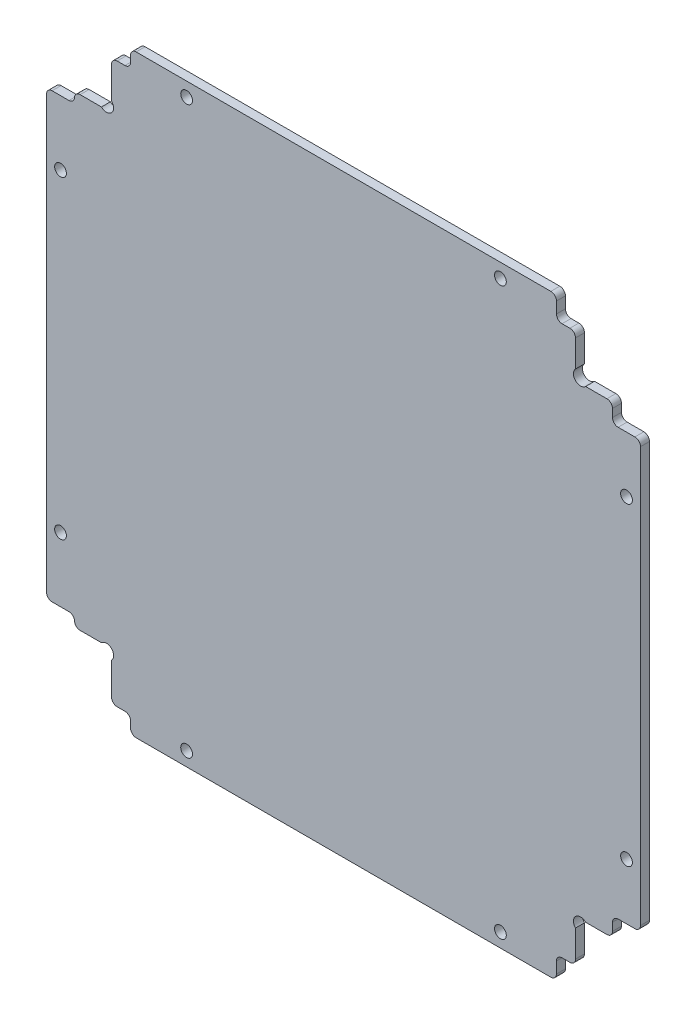
SolidWorks part; units mm, degrees
ref_plane "Front Plane" through (0, 0, 0) normal (0, 0, 1) x (1, 0, 0)
ref_plane "Top Plane" through (0, 0, 0) normal (0, 1, 0) x (1, 0, 0)
ref_plane "Right Plane" through (0, 0, 0) normal (1, 0, 0) x (0, 0, -1)
sketch "Sketch1" plane through (0, 0, 0) normal (0, 0, 1) x (1, 0, 0)
  line L0 (53, 53) -> (-53, -53) construction
  line L1 (53, 53) -> (-53, 53)
  line L2 (53, 53) -> (53, -53)
  line L3 (53, -53) -> (-53, -53)
  line L4 (-53, 53) -> (-53, -53)
  point P4 (0, 0)
  dimension "D1" = 106
  dimension "D2" = 106
extrude "mainOutline" add sketch "Sketch1" along normal blind 1.6
sketch "axisLabels" plane through (0, 0, 0) normal (0, 0, -1) x (-1, 0, 0)
  text T0 "+Y"
  text T1 "+X"
sketch "Sketch4" plane through (0, 0, 0) normal (0, 0, -1) x (-1, 0, 0)
  line L1 (-41.4, -41.4) -> (-48, -41.4)
  line L3 (-41.4, -49) -> (-41.4, -41.4)
  line L5 (-60.1065, -39) -> (-49.9975, -39)
  line L7 (-39, -61.4521) -> (-39, -49.9)
  line L9 (39, -56.2753) -> (39, -49.9)
  line L10 (-53, 53) -> (53, 53) construction
  line L11 (41.4, -49.9) -> (41.4, -41.4)
  line L12 (-53, -53) -> (-53, 53) construction
  line L13 (41.4, -41.4) -> (48, -41.4)
  line L15 (48, -40.5) -> (55.5177, -40.5)
  line L17 (55.3838, 40.5) -> (48, 40.5)
  line L19 (39, 57.6877) -> (39, 49.9)
  line L21 (-39, 59.8804) -> (-39, 49.9)
  line L23 (-56.8428, 39) -> (-49.9975, 39)
  line L25 (-41.4, 41.4) -> (-41.4, 49)
  line L27 (-48, 41.4) -> (-41.4, 41.4)
  line L29 (41.4, 49.9) -> (41.4, 41.4)
  line L31 (48, 41.4) -> (41.4, 41.4)
  line L32 (-48, 41.4) -> (-48, 39)
  line L33 (-48, 39) -> (-49.9975, 39)
  line L34 (-41.4, 49) -> (-39, 49)
  line L35 (-39, 49) -> (-39, 49.9)
  line L36 (48, 40.5) -> (48, 41.4)
  line L37 (39, 49.9) -> (41.4, 49.9)
  line L38 (48, -40.5) -> (48, -41.4)
  line L39 (39, -49.9) -> (41.4, -49.9)
  line L40 (-41.4, -49) -> (-39, -49)
  line L41 (-39, -49) -> (-39, -49.9)
  line L42 (-49.9975, -39) -> (-48, -39)
  line L43 (-48, -39) -> (-48, -41.4)
  line L44 (-39, 59.8804) -> (-56.8428, 59.8804)
  line L45 (-56.8428, 59.8804) -> (-56.8428, 39)
  line L46 (53, 53) -> (53, -53) construction
  line L47 (-60.1065, -39) -> (-60.1065, -61.4521)
  line L48 (-60.1065, -61.4521) -> (-39, -61.4521)
  line L49 (39, -56.2753) -> (55.5177, -56.2753)
  line L50 (55.5177, -56.2753) -> (55.5177, -40.5)
  line L51 (55.3838, 40.5) -> (55.3838, 57.6877)
  line L52 (55.3838, 57.6877) -> (39, 57.6877)
  line L53 (53, -53) -> (-53, -53) construction
  dimension "D1" = 14
  dimension "D2" = 11.6
  dimension "D3" = 5
  dimension "D4" = 12.5
  dimension "D5" = 11.6
  dimension "D6" = 3.1
  dimension "D7" = 12.5
  dimension "D8" = 14
  dimension "D9" = 3.1
  dimension "D10" = 5
  dimension "D11" = 11.6
  dimension "D12" = 11.6
  dimension "D13" = 14
  dimension "D14" = 14
  dimension "D15" = 11.6
  dimension "D16" = 11.6
  dimension "D17" = 5
  dimension "D18" = 4
  dimension "D19" = 14
  dimension "D20" = 14
  dimension "D21" = 11.6
  dimension "D22" = 11.6
  dimension "D23" = 4
  dimension "D24" = 5
extrude "railCutouts" cut sketch "Sketch4" against normal through all
sketch "Sketch5" plane through (0, 0, 0) normal (0, 0, -1) x (-1, 0, 0)
  line L0 (-48.898, -39.898) -> (-52.4015, -43.4015) construction
  line L1 (-48, -40.7961) -> (-51.5035, -44.2995) construction
  line L2 (-49.7961, -39) -> (-53.2995, -42.5035) construction
  line L3 (-48, -41.4) -> (-48, -39) construction
  line L4 (-48, 39) -> (-48, 41.4) construction
  line L5 (-42.298, -42.298) -> (-45.4445, -45.4445) construction
  line L6 (-41.4, -43.1961) -> (-44.5465, -46.3425)
  line L7 (-43.1961, -41.4) -> (-46.3425, -44.5465)
  line L8 (-39.898, -49.898) -> (-42.6199, -52.6199) construction
  line L9 (-39, -50.7961) -> (-41.7219, -53.5179) construction
  line L10 (-40.7961, -49) -> (-43.5179, -51.7219) construction
  line L11 (39.898, -50.798) -> (41.4231, -52.3231) construction
  line L12 (40.7961, -49.9) -> (42.3212, -51.4251) construction
  line L13 (39, -51.6961) -> (40.5251, -53.2212) construction
  line L14 (42.298, -42.298) -> (44.0402, -44.0402) construction
  line L15 (43.1961, -41.4) -> (44.9382, -43.1422)
  line L16 (41.4, -43.1961) -> (43.1422, -44.9382)
  line L17 (48.898, -41.398) -> (49.9793, -42.4793) construction
  line L18 (49.7961, -40.5) -> (50.8774, -41.5813) construction
  line L19 (48, -42.2961) -> (49.0813, -43.3774) construction
  line L20 (48.898, 41.398) -> (50.5001, 43.0001) construction
  line L21 (48, 42.2961) -> (49.602, 43.8981) construction
  line L22 (49.7961, 40.5) -> (51.3981, 42.102) construction
  line L23 (42.298, 42.298) -> (44.029, 44.029) construction
  line L24 (41.4, 43.1961) -> (43.131, 44.927)
  line L25 (43.1961, 41.4) -> (44.927, 43.131)
  line L26 (39.898, 50.798) -> (41.2638, 52.1638) construction
  line L27 (39, 51.6961) -> (40.3658, 53.0618) construction
  line L28 (40.7961, 49.9) -> (42.1618, 51.2658) construction
  line L29 (-48.898, 39.898) -> (-50.0606, 41.0606) construction
  line L30 (-49.7961, 39) -> (-50.9587, 40.1626) construction
  line L31 (-48, 40.7961) -> (-49.1626, 41.9587) construction
  line L32 (-42.298, 42.298) -> (-43.7968, 43.7968) construction
  line L33 (-43.1961, 41.4) -> (-44.6948, 42.8988)
  line L34 (-41.4, 43.1961) -> (-42.8988, 44.6948)
  line L35 (-39.898, 49.898) -> (-41.256, 51.256) construction
  line L36 (-40.7961, 49) -> (-42.154, 50.358) construction
  line L37 (-39, 50.7961) -> (-40.358, 52.154) construction
  line L38 (-41.4, 41.4) -> (-41.4, 49) construction
  line L39 (-39, 49) -> (-39, 53) construction
  line L40 (39, 53) -> (39, 49.9) construction
  line L41 (41.4, 49.9) -> (41.4, 41.4) construction
  line L42 (48, 41.4) -> (48, 40.5) construction
  line L43 (39, -49.9) -> (39, -53) construction
  line L44 (41.4, -41.4) -> (41.4, -49.9) construction
  line L45 (53, -40.5) -> (48, -40.5) construction
  line L46 (-39, -53) -> (-39, -49) construction
  line L47 (-41.4, -49) -> (-41.4, -41.4) construction
  arc A0 (-48, -40.7961) -> (-49.7961, -39) centre (-48.898, -39.898) ccw construction
  arc A1 (-53.2995, -42.5035) -> (-51.5035, -44.2995) centre (-52.4015, -43.4015) ccw construction
  arc A2 (-41.4, -43.1961) -> (-43.1961, -41.4) centre (-42.298, -42.298) ccw
  arc A3 (-46.3425, -44.5465) -> (-44.5465, -46.3425) centre (-45.4445, -45.4445) ccw
  arc A4 (-39, -50.7961) -> (-40.7961, -49) centre (-39.898, -49.898) ccw construction
  arc A5 (-43.5179, -51.7219) -> (-41.7219, -53.5179) centre (-42.6199, -52.6199) ccw construction
  arc A6 (40.7961, -49.9) -> (39, -51.6961) centre (39.898, -50.798) ccw construction
  arc A7 (40.5251, -53.2212) -> (42.3212, -51.4251) centre (41.4231, -52.3231) ccw construction
  arc A8 (43.1961, -41.4) -> (41.4, -43.1961) centre (42.298, -42.298) ccw
  arc A9 (43.1422, -44.9382) -> (44.9382, -43.1422) centre (44.0402, -44.0402) ccw
  arc A10 (49.7961, -40.5) -> (48, -42.2961) centre (48.898, -41.398) ccw construction
  arc A11 (49.0813, -43.3774) -> (50.8774, -41.5813) centre (49.9793, -42.4793) ccw construction
  arc A12 (48, 42.2961) -> (49.7961, 40.5) centre (48.898, 41.398) ccw construction
  arc A13 (51.3981, 42.102) -> (49.602, 43.8981) centre (50.5001, 43.0001) ccw construction
  arc A14 (41.4, 43.1961) -> (43.1961, 41.4) centre (42.298, 42.298) ccw
  arc A15 (44.927, 43.131) -> (43.131, 44.927) centre (44.029, 44.029) ccw
  arc A16 (39, 51.6961) -> (40.7961, 49.9) centre (39.898, 50.798) ccw construction
  arc A17 (42.1618, 51.2658) -> (40.3658, 53.0618) centre (41.2638, 52.1638) ccw construction
  arc A18 (-49.7961, 39) -> (-48, 40.7961) centre (-48.898, 39.898) ccw construction
  arc A19 (-49.1626, 41.9587) -> (-50.9587, 40.1626) centre (-50.0606, 41.0606) ccw construction
  arc A20 (-43.1961, 41.4) -> (-41.4, 43.1961) centre (-42.298, 42.298) ccw
  arc A21 (-42.8988, 44.6948) -> (-44.6948, 42.8988) centre (-43.7968, 43.7968) ccw
  arc A22 (-40.7961, 49) -> (-39, 50.7961) centre (-39.898, 49.898) ccw construction
  arc A23 (-40.358, 52.154) -> (-42.154, 50.358) centre (-41.256, 51.256) ccw construction
  point P2 (-50.6498, -41.6498)
  point P9 (-43.8713, -43.8713)
  point P17 (-41.259, -51.259)
  point P24 (40.6606, -51.5606)
  point P31 (43.1691, -43.1691)
  point P38 (49.4387, -41.9387)
  point P45 (49.699, 42.199)
  point P52 (43.1635, 43.1635)
  point P59 (40.5809, 51.4809)
  point P66 (-49.4793, 40.4793)
  point P73 (-43.0474, 43.0474)
  point P80 (-40.577, 50.577)
  point P99 (0, 0)
  point P121 (0, 0)
  point P122 (0, 0)
  dimension "D14" = 1.27
  dimension "D1" = 45
  dimension "D3" = 45
  dimension "D4" = 45
  dimension "D5" = 45
  dimension "D6" = 45
  dimension "D7" = 45
  dimension "D8" = 45
  dimension "D9" = 45
  dimension "D10" = 45
  dimension "D11" = 45
  dimension "D12" = 45
  dimension "D13" = 45
extrude "dogbones" cut sketch "Sketch5" against normal through all
sketch "Sketch6" plane through (0, 0, 0) normal (0, 0, -1) x (-1, 0, 0)
  line L0 (-39, 50) -> (-39, 53) construction
  line L1 (-39, 49) -> (-39, 53) construction
  line L2 (-39, 53) -> (39, 53) construction
  line L3 (-40, 50) -> (-40, 53)
  line L4 (-38, 50) -> (-38, 53)
  line L5 (-49, 39) -> (-53, 39) construction
  line L6 (-53, 39) -> (-48, 39) construction
  line L7 (-49, 38) -> (-53, 38)
  line L8 (-49, 40) -> (-53, 40)
  line L9 (-49, -39) -> (-55.2142, -39) construction
  line L10 (-48, -39) -> (-53, -39) construction
  line L11 (-49, -40) -> (-55.2142, -40)
  line L12 (-49, -38) -> (-55.2142, -38)
  line L13 (-39, -50) -> (-39, -53.9161) construction
  line L14 (-39, -53) -> (-39, -49) construction
  line L15 (-38, -50) -> (-38, -53.9161)
  line L16 (-40, -50) -> (-40, -53.9161)
  line L17 (39, -50.9) -> (39, -54.538) construction
  line L18 (39, -49.9) -> (39, -53) construction
  line L19 (40, -50.9) -> (40, -54.538)
  line L20 (38, -50.9) -> (38, -54.538)
  line L21 (49, -40.5) -> (54.2026, -40.5) construction
  line L22 (53, -40.5) -> (48, -40.5) construction
  line L23 (49, -39.5) -> (54.2026, -39.5)
  line L24 (49, -41.5) -> (54.2026, -41.5)
  line L25 (49, 40.5) -> (54.5566, 40.5) construction
  line L26 (48, 40.5) -> (53, 40.5) construction
  line L27 (49, 41.5) -> (54.5566, 41.5)
  line L28 (49, 39.5) -> (54.5566, 39.5)
  line L29 (39, 50.9) -> (39, 55.8281) construction
  line L30 (39, 53) -> (39, 49.9) construction
  line L31 (38, 50.9) -> (38, 55.8281)
  line L32 (40, 50.9) -> (40, 55.8281)
  line L33 (-48, -41.4) -> (-48, -39) construction
  line L34 (-39, -49) -> (-41.4, -49) construction
  line L35 (41.4, -49.9) -> (39, -49.9) construction
  line L36 (48, -40.5) -> (48, -41.4) construction
  line L37 (48, 41.4) -> (48, 40.5) construction
  line L38 (39, 49.9) -> (41.4, 49.9) construction
  arc A0 (-40, 50) -> (-38, 50) centre (-39, 50) ccw
  arc A1 (-38, 53) -> (-40, 53) centre (-39, 53) ccw
  arc A2 (-49, 38) -> (-49, 40) centre (-49, 39) ccw
  arc A3 (-53, 40) -> (-53, 38) centre (-53, 39) ccw
  arc A4 (-49, -40) -> (-49, -38) centre (-49, -39) ccw
  arc A5 (-55.2142, -38) -> (-55.2142, -40) centre (-55.2142, -39) ccw
  arc A6 (-38, -50) -> (-40, -50) centre (-39, -50) ccw
  arc A7 (-40, -53.9161) -> (-38, -53.9161) centre (-39, -53.9161) ccw
  arc A8 (40, -50.9) -> (38, -50.9) centre (39, -50.9) ccw
  arc A9 (38, -54.538) -> (40, -54.538) centre (39, -54.538) ccw
  arc A10 (49, -39.5) -> (49, -41.5) centre (49, -40.5) ccw
  arc A11 (54.2026, -41.5) -> (54.2026, -39.5) centre (54.2026, -40.5) ccw
  arc A12 (49, 41.5) -> (49, 39.5) centre (49, 40.5) ccw
  arc A13 (54.5566, 39.5) -> (54.5566, 41.5) centre (54.5566, 40.5) ccw
  arc A14 (38, 50.9) -> (40, 50.9) centre (39, 50.9) ccw
  arc A15 (40, 55.8281) -> (38, 55.8281) centre (39, 55.8281) ccw
  point P6 (-39, 51.5)
  point P11 (-51, 39)
  point P21 (-52.1071, -39)
  point P30 (-39, -51.958)
  point P39 (39, -52.719)
  point P48 (51.6013, -40.5)
  point P57 (51.7783, 40.5)
  point P66 (39, 53.364)
  point P75 (-39, 49)
  dimension "D1" = 1
extrude "solarFillets" cut sketch "Sketch6" against normal through all
fillet "handlingFillets" radius 1 16 edges at (-41.4, -49.9, 0.8) (-38, -53, 0.8) (-53, -39.5, 0.8) (-48, -41.4, 0.8) (-48, 41.4, 0.8) (-53, 39.5, 0.8) (-41.4, 49.9, 0.8) (-38, 53, 0.8) (38, 53, 0.8) (41.4, 49, 0.8) (48, 41.4, 0.8) (53, 38, 0.8) (53, -38, 0.8) (48, -41.4, 0.8) (41.4, -49, 0.8) (38, -53, 0.8)
sketch "Sketch7" plane through (0, 0, 1.6) normal (0, 0, 1) x (1, 0, 0)
  line L0 (-37, -53) -> (37, -53) construction
  line L1 (-53, 38.5) -> (-53, -38.5) construction
  line L2 (37, 53) -> (-37, 53) construction
  line L3 (-31.37, 28.67) -> (-31.37, 31.21) construction
  line L4 (-31.37, 31.21) -> (-28.83, 31.21) construction
  line L5 (-28.83, 31.21) -> (-28.83, 28.67) construction
  line L6 (-28.83, 28.67) -> (-31.37, 28.67) construction
  line L7 (-31.37, 28.67) -> (-28.83, 31.21) construction
  circle A1 centre (-28.4723, -17.925) radius 0.8
  circle A3 centre (-28.4723, -33.775) radius 0.8
  circle A5 centre (-31.37, 28.67) radius 0.425
  circle A7 centre (-28.83, 28.67) radius 0.425
  circle A9 centre (-30.1, 29.94) radius 0.425
  circle A10 centre (-28.83, 31.21) radius 0.425
  circle A11 centre (-31.37, 31.21) radius 0.425
  circle A12 centre (-31.37, 21.27) radius 0.425
  circle A13 centre (-28.83, 21.27) radius 0.425
  circle A14 centre (-30.1, 22.54) radius 0.425
  circle A15 centre (-28.83, 23.81) radius 0.425
  circle A16 centre (-31.37, 23.81) radius 0.425
  circle A17 centre (-31.37, 13.87) radius 0.425
  circle A18 centre (-28.83, 13.87) radius 0.425
  circle A19 centre (-30.1, 15.14) radius 0.425
  circle A20 centre (-28.83, 16.41) radius 0.425
  circle A21 centre (-31.37, 16.41) radius 0.425
  point P13 (-30.1, 29.94)
  dimension "D8" = 1.6
  dimension "D9" = 3
  dimension "D6" = 0.85
  dimension "D1" = 19.225
  dimension "D2" = 24.5277
  dimension "D3" = 15.85
  dimension "D4" = 23.06
  dimension "D5" = 22.9
  dimension "D7" = 2.54
  dimension "D10" = 7.4
extrude "connectorHoles" [suppressed] cut sketch "Sketch7" against normal through all
hole_wizard "M2 Clearance Hole1" positions "Sketch8" profile "Sketch9" hole size "M2" standard "ANSI Metric" end condition through all
sketch "Sketch8" plane through (0, 0, 0) normal (0, 0, -1) x (-1, 0, 0)
  line L0 (53, 38.5) -> (53, -38.5) construction
  line L1 (37, -53) -> (-37, -53) construction
  line L2 (-53, -37) -> (-53, 37) construction
  line L3 (53, 0) -> (-53, 0) construction
  line L5 (0, -53) -> (0, -11.6379) construction
  point P0 (50.5, -28)
  point P1 (28, -50.5)
  point P5 (-50.5, -28)
  point P30 (-28, -50.5)
  point P31 (-28, 50.5)
  point P32 (-50.5, 28)
  point P33 (28, 50.5)
  point P34 (50.5, 28)
  dimension "D1" = 2.5
  dimension "D2" = 2.5
  dimension "D4" = 2.5
  dimension "D5" = 25
  dimension "D6" = 25
  dimension "D7" = 25
sketch "Sketch9" plane through (-50.5, -28, 0) normal (1, 0, 0) x (0, 1, 0)
  line L0 (0, 0) -> (0, 1.6)
  line L1 (0, 1.6) -> (1.05, 1.6)
  line L2 (1.05, 1.6) -> (1.05, 0)
  line L5 (1.05, 0) -> (0, 0)
  line L11 (0, -6.35) -> (0, 107.95) construction
  dimension "Thru Hole Dia." = 2.1
  dimension "Thru Hole Depth" = 1.6
